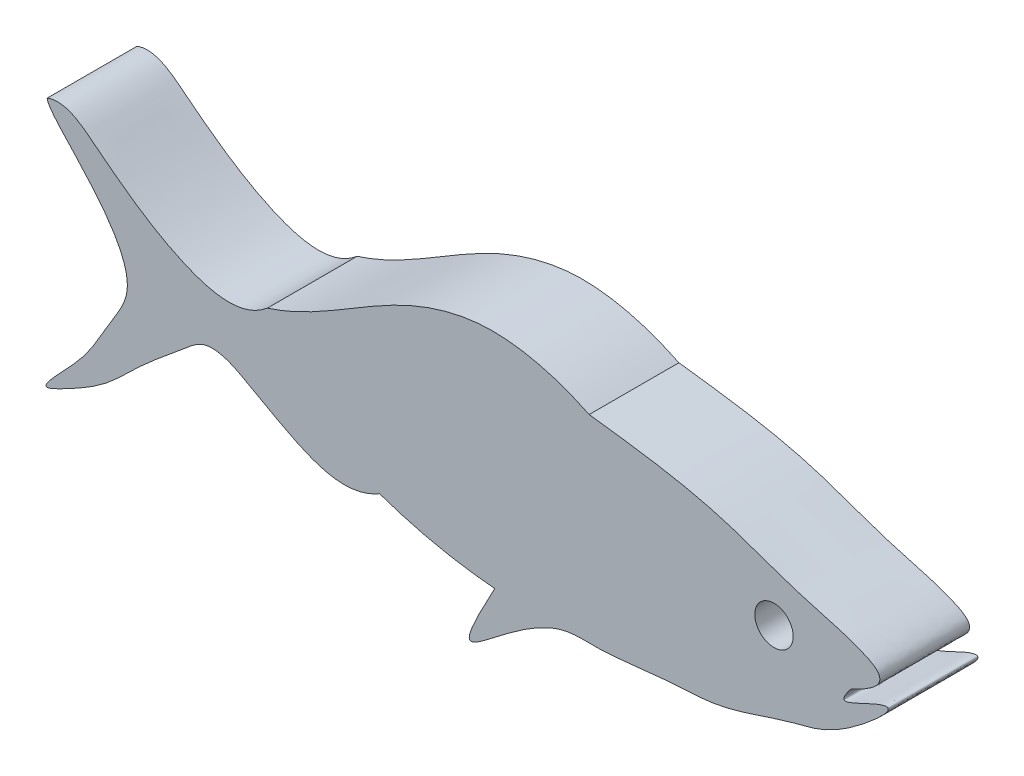
SolidWorks part; units mm, degrees
ref_plane "Front Plane" through (0, 0, 0) normal (0, 0, 1) x (1, 0, 0)
ref_plane "Top Plane" through (0, 0, 0) normal (0, 1, 0) x (1, 0, 0)
ref_plane "Right Plane" through (0, 0, 0) normal (1, 0, 0) x (0, 0, -1)
sketch "Sketch1" plane through (0, 0, 0) normal (0, 0, 1) x (1, 0, 0)
  line L0 (-20.3378, 0.3214) -> (19.6622, 0.3214) construction
  circle A0 centre (12.4428, 0.7274) radius 0.8562
  spline S0 degree 2 poles (0, -4.0717) (-2.643, -3.8543) (-5.1342, -2.9801) knots 0 0 0 1 1 1
  spline S1 degree 3 poles (-5.1342, -2.9801) (-6.6003, -3.8367) (-8.6242, -3.0212) (-10.7857, -1.7826) (-11.9783, -1.1232) (-13.0363, -1.0404) (-14.2669, -2.1074) (-15.5757, -3.1311) (-17.2085, -4.7941) (-18.2515, -5.4831) (-20.5133, -6.6446) (-18.9624, -5.011) (-18.0514, -4.0175) (-17.1778, -2.3993) (-15.1712, 0.6857) (-19.9498, 4.1899) (-19.9447, 4.8844) knots 0 0 0 0 0.13839 0.206906 0.246749 0.271841 0.30508 0.398465 0.442724 0.524565 0.560246 0.603348 0.653723 0.724779 0.775116 1 1 1 1
  spline S2 degree 3 poles (-19.9447, 4.8844) (-19.1075, 5.2078) (-17.73, 4.0377) (-15.8934, 2.6545) (-13.4503, 1.2043) (-11.2569, 0.7346) (-10.1331, 1.6835) knots 0 0 0 0 0.228016 0.426643 0.652701 1 1 1 1
  spline S3 degree 3 poles (-10.1331, 1.6835) (-7.8218, 2.4147) (-5.0594, 4.7659) (0.0229, 6.2122) (2.7962, 5.427) (4.2068, 4.7465) knots 0 0 0 0 0.466637 0.691355 1 1 1 1
  spline S4 degree 3 poles (0, -4.0717) (-2.9491, -9.489) (1.1029, -3.8671) (5.0694, -4.1491) (7.3448, -3.742) (10.2579, -3.7274) (13.0869, -2.5279) (15.1655, -2.2915) (18.1568, 0.3448) (16.4166, -0.2008) (14.9492, -1.1814) (15.8867, 0) knots 0 0 0 0 0.296366 0.351295 0.477375 0.561695 0.696649 0.802298 0.898253 0.910817 1 1 1 1
  spline S5 degree 3 poles (15.8867, 0) (17.9046, 0.9016) (16.2577, 1.8601) (13.4422, 2.4651) (9.5181, 4.0902) (6.1976, 4.4926) (4.2068, 4.7465) knots 0 0 0 0 0.160361 0.331409 0.596131 1 1 1 1
  dimension "D1" = 40
extrude "Boss-Extrude1" add sketch "Sketch1" along normal blind 4
ref_plane "Plane2" through (0, -10, 0) normal (0, 1, 0) x (1, 0, 0)
sketch "Sketch3" plane through (0, -10, 0) normal (0, 1, 0) x (1, 0, 0)
  line L0 (-5.1342, -4) -> (-5.1342, 0) construction
  circle A0 centre (-5.1342, -2) radius 1.5
  point P2 (-5.1342, -2)
  dimension "D1" = 3
extrude "Cut-Extrude1" cut sketch "Sketch3" along normal blind 9
